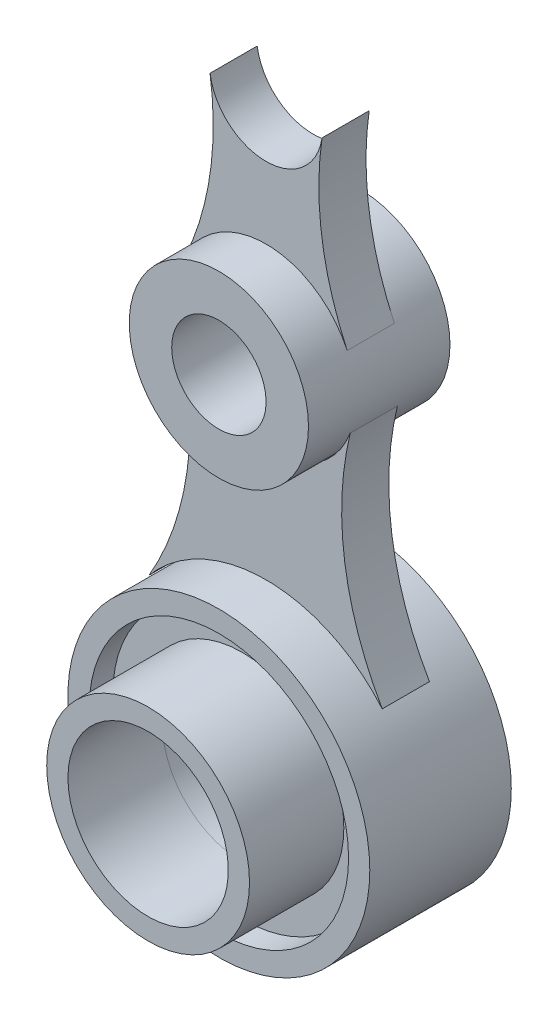
SolidWorks part; units mm, degrees
ref_plane "Front Plane" through (0, 0, 0) normal (0, 0, 1) x (1, 0, 0)
ref_plane "Top Plane" through (0, 0, 0) normal (0, 1, 0) x (1, 0, 0)
ref_plane "Right Plane" through (0, 0, 0) normal (1, 0, 0) x (0, 0, -1)
sketch "Sketch1" plane through (0, 0, 0) normal (0, 0, 1) x (1, 0, 0)
  line L0 (3.8578, -54.9324) -> (3.8578, 71.0676) construction
  line L1 (3.8578, 52.0676) -> (50003.8578, 52.0676) construction
  line L2 (3.8578, -22.9324) -> (50003.8578, -22.9324) construction
  point P2 (3.8578, 52.0676)
  point P3 (3.8578, -22.9324)
  point P7 (3.8578, -22.9324)
  point P10 (3.8578, 52.0676)
  dimension "D1" = 126
  dimension "D2" = 19
  dimension "D3" = 32
sketch "Sketch2" plane through (0, 0, 0) normal (0, 0, 1) x (1, 0, 0)
  circle A1 centre (3.8578, 52.0676) radius 19
  circle A2 centre (3.8578, -22.9324) radius 32
  dimension "D1" = 38
  dimension "D2" = 64
extrude "Boss-Extrude1" add sketch "Sketch2" along normal blind 30
ref_plane "Plane1" through (0, 0, 10) normal (0, 0, 1) x (1, 0, 0)
sketch "Sketch3" plane through (0, 0, 10) normal (0, 0, 1) x (1, 0, 0)
  arc A0 (21.7194, 45.2627) -> (28.4994, -1.975) centre (83.8927, 30.0809) ccw
  circle A2 centre (3.8578, -22.9324) radius 32 construction
  arc A3 (-14.9088, 48.4398) -> (21.7194, 45.2627) centre (3.8578, 52.0676) ccw
  arc A4 (28.4994, -1.975) -> (-24.9152, -8.1493) centre (3.8578, -22.9324) ccw
  arc A5 (-14.9088, 48.4398) -> (-24.9152, -8.1493) centre (-76.2257, 30.1029) cw
  arc A6 (21.0715, 60.1104) -> (-13.356, 60.1104) centre (3.8578, 52.0676) ccw
  arc A7 (-8.0154, 96.4824) -> (15.7309, 96.4824) centre (3.8578, 98.2225) ccw
  arc A8 (21.0715, 60.1104) -> (15.7309, 96.4824) centre (79.0545, 87.2022) cw
  arc A9 (-13.356, 60.1104) -> (-8.0154, 96.4824) centre (-71.339, 87.2022) ccw
  point P3 (0, 0)
  point P4 (3.8578, 98.2225)
  point P22 (0, 0)
  point P24 (0, 0)
  dimension "D1" = 64
  dimension "D2" = 64
  dimension "D3" = 38
  dimension "D5" = 12
extrude "Boss-Extrude2" add sketch "Sketch3" along normal blind 10 contours A9 A6 A8 A7 | A3 A5 A4 A0
ref_plane "Plane2" through (0, 0, 25) normal (0, 0, 1) x (1, 0, 0)
sketch "Sketch4" plane through (0, 0, 25) normal (0, 0, 1) x (1, 0, 0)
  circle A0 centre (3.8578, -22.9324) radius 27.5
  dimension "D1" = 55
extrude "Cut-Extrude1" cut sketch "Sketch4" along normal blind 5
sketch "Sketch5" plane through (0, 0, 25) normal (0, 0, 1) x (1, 0, 0)
  circle A0 centre (3.8578, -22.9324) radius 21.5
  dimension "D1" = 43
extrude "Boss-Extrude3" add sketch "Sketch5" along normal blind 20
sketch "Sketch6" plane through (0, 0, 0) normal (0, 0, 1) x (1, 0, 0)
  circle A0 centre (3.8578, -22.9324) radius 17
  circle A1 centre (3.8578, 52.0676) radius 10
  dimension "D1" = 34
  dimension "D2" = 20
extrude "Cut-Extrude2" cut sketch "Sketch6" along normal through all
